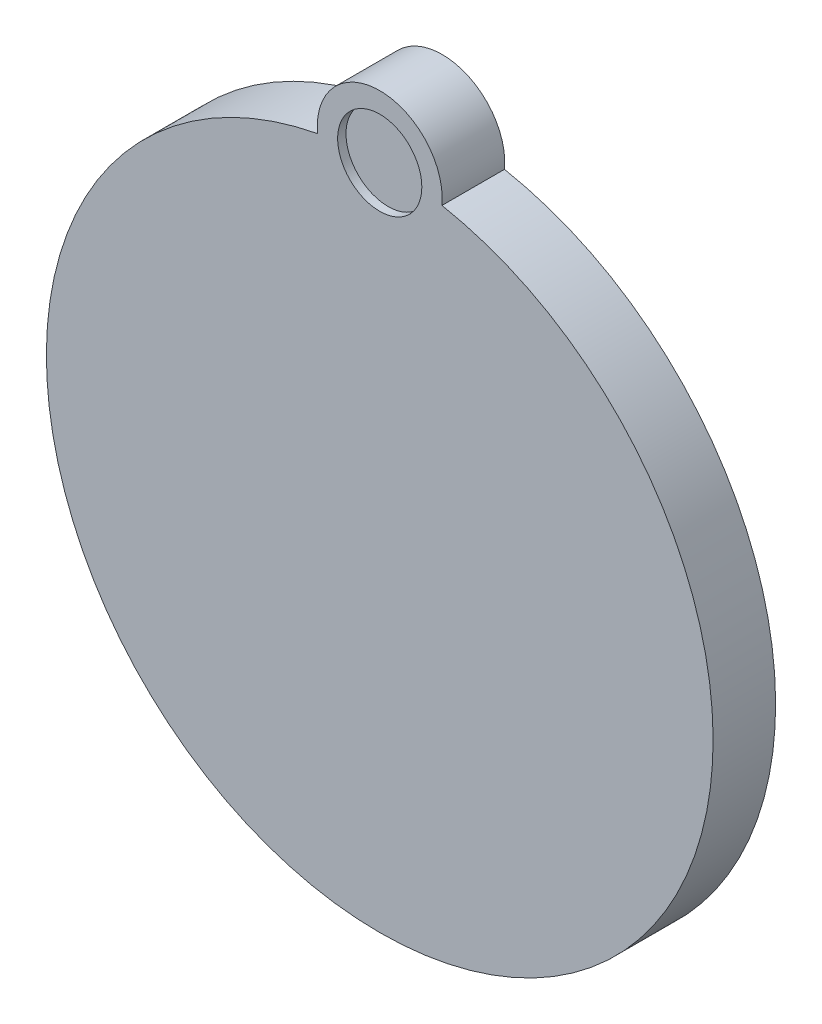
SolidWorks part; units mm, degrees
ref_plane "正面" through (0, 0, 0) normal (0, 0, 1) x (1, 0, 0)
ref_plane "平面" through (0, 0, 0) normal (0, 1, 0) x (1, 0, 0)
ref_plane "右側面" through (0, 0, 0) normal (1, 0, 0) x (0, 0, -1)
sketch "ｽｹｯﾁ4" plane through (0, 0, 0) normal (0, 0, 1) x (1, 0, 0)
  arc A1 (-14.9339, -1.4063) -> (9.9804, -0.625) centre (0, -80) ccw
  arc A3 (14.9339, -1.4063) -> (-14.9339, -1.4063) centre (0, 0) ccw
  dimension "D4" = 30
  dimension "D2" = 80
extrude "ﾎﾞｽ - 押し出し1" add sketch "ｽｹｯﾁ4" along normal blind 15
sketch "ｽｹｯﾁ10" plane through (0, 0, 15) normal (0, 0, 1) x (1, 0, 0)
  circle A0 centre (0, 0) radius 10.1
  dimension "D1" = 20.2
extrude "ｶｯﾄ - 押し出し3" cut sketch "ｽｹｯﾁ10" against normal blind 2
